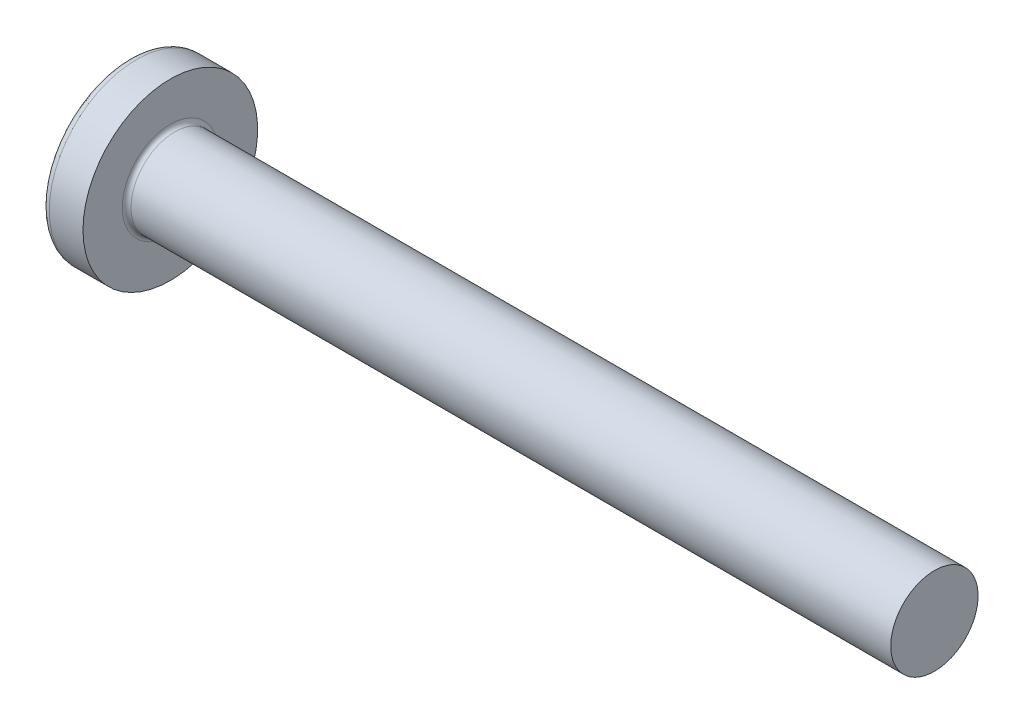
SolidWorks part; units mm, degrees
material "普通碳钢"
ref_plane "Plane1" through (0, 0, 0) normal (0, 0, 1) x (1, 0, 0)
ref_plane "Plane2" through (0, 0, 0) normal (0, 1, 0) x (1, 0, 0)
ref_plane "Plane3" through (0, 0, 0) normal (1, 0, 0) x (0, 0, -1)
sketch "BodySke" plane through (0, 0, 0) normal (0, 0, 1) x (1, 0, 0)
  line L0 (3.1, 2) -> (3.1, 4)
  line L1 (3.45, 6.35) -> (3.45, -3.175) construction
  line L2 (-25.4, 0) -> (127, 0) construction
  line L3 (38.1, 0) -> (0, 0)
  line L4 (3.1, 2) -> (38.1, 2)
  line L5 (38.1, 2) -> (38.1, 0)
  line L6 (1.5553, 4) -> (3.1, 4)
  line L8 (32.1, 6.35) -> (32.1, -3.175) construction
  arc A0 (1.2654, 3.8534) -> (0, 0) centre (6.5, 0) ccw
  arc A2 (1.2654, 3.8534) -> (1.5553, 4) centre (1.5553, 3.64) cw
  dimension "Head_fillet_rad" = 0.36
  dimension "Head_crown_rad" = 6.5
  dimension "Head_ht" = 3.1
  dimension "Diameter" = 4
  dimension "Length" = 35
  dimension "Head_dia" = 8
  dimension "Advance" = 0.7
  dimension "Thread_nom" = 6
revolve "Base-Revolve" add sketch "BodySke"
cosmetic thread "ThreadCosmetic" [suppressed]
fillet "Fillet1" radius 0.2 1 edges at (3.1, 0, 2)
sketch "Sketch3" plane through (0, 0, 0) normal (1, 0, 0) x (0, 0, -1)
  line L0 (0.515, -2.15) -> (-0.515, -2.15)
  line L1 (0.515, -2.15) -> (0.515, 2.15)
  line L2 (-0.515, 2.15) -> (0.515, 2.15)
  line L3 (-0.515, 2.15) -> (-0.515, -2.15)
  dimension "D1" = 2.15
  dimension "Cross_dia" = 4.3
  dimension "D2" = 0.515
  dimension "Cross_width" = 1.03
ref_plane "Plane4" through (2.34, 0, 0) normal (1, 0, 0) x (0, 0, -1)
sketch "Sketch4" plane through (2.34, 0, 0) normal (1, 0, 0) x (0, 0, -1)
  line L0 (0.515, -0.9833) -> (-0.515, -0.9833)
  line L1 (0.515, -0.9833) -> (0.515, 0.9833)
  line L2 (-0.515, 0.9833) -> (0.515, 0.9833)
  line L3 (-0.515, 0.9833) -> (-0.515, -0.9833)
  dimension "D1" = 1.03
  dimension "D2" = 1.9666
  dimension "D3" = 0.515
  dimension "D4" = 0.9833
loft "Recess" cut profiles "Sketch3", "Sketch4"
pattern_circular "RecPat" count 2 every 90 about axis through (0, 0, 0) along (1, 0, 0) of "Recess"
sketch "RecCorSke" plane through (0, 0, 0) normal (0, 0, 1) x (1, 0, 0)
  line L0 (-3.175, 0) -> (15.875, 0) construction
  line L1 (-25.4, 0) -> (127, 0) construction
  line L2 (0, 0) -> (0, 1.0146)
  line L3 (0, 1.0146) -> (2.34, 0.851)
  line L4 (2.34, 0.851) -> (2.6165, 0)
  line L5 (2.6165, 0) -> (0, 0)
  dimension "Diameter" = 1.702
  dimension "Depth" = 2.34
  dimension "Draft_angle" = 4
  dimension "Bottom_angle" = 18
revolve "RecessCore" cut sketch "RecCorSke" angle 360 about L0
sketch "ThdSchSke" plane through (0, 0, 0) normal (0, 0, 1) x (1, 0, 0)
  line L0 (27.1, -1.61) -> (26.8269, -2)
  line L1 (27.1, -1.61) -> (27.3731, -2)
  line L2 (27.3731, -2) -> (27.3731, -2.5)
  line L3 (-3.175, 0) -> (5.1513, 0) construction
  line L5 (27.3731, -2.5) -> (26.8269, -2.5)
  line L6 (26.8269, -2.5) -> (26.8269, -2)
  dimension "Thread_minor" = 3.22
  dimension "Diameter" = 4
  dimension "Start" = 27.1
  dimension "SideAngle" = 55
  dimension "VeeAngle" = 70
  dimension "Overcut" = 5
revolve "ThreadSchematic" [suppressed] cut sketch "ThdSchSke" angle 360 about L3
pattern_linear "ThdSchPat" [suppressed]
sketch "草图1" plane through (38.1, 0, 0) normal (1, 0, 0) x (0, 0, -1)
  circle A0 centre (0, 0) radius 2 construction
  circle A1 centre (0, 0) radius 2
equation "\"D1@Sketch3\" = \"Cross_dia@Sketch3\" / 2"
equation "\"D2@Sketch3\" = \"Cross_width@Sketch3\" / 2"
equation "\"Depth@RecCorSke\" = \"Cross_depth@Plane4\""
equation "\"D1@Sketch4\" = \"Cross_width@Sketch3\""
equation "\"D2@Sketch4\" = \"Cross_dia@Sketch3\" - 2.0 * \"Cross_depth@Plane4\" * tan(26.5  * 0.017453292)"
equation "\"D3@Sketch4\" = \"D1@Sketch4\" / 2"
equation "\"D4@Sketch4\" = \"D2@Sketch4\" / 2"
equation "\"Thread_length@ThreadCosmetic\" = ((sgn( (\"Length@BodySke\" - \"Advance@BodySke\" * 2.0 ) - \"Thread_nom@BodySke\" )-1)*( (\"Length@BodySke\" - \"Advance@BodySke\" * 2.0 ) - \"Thread_nom@BodySke\" ))/-2+ \"Thread_nom@BodySke\""
equation "\"Thread_minor@ThdSchSke\" = \"Thread_minor@ThreadCosmetic\""
equation "\"Diameter@ThdSchSke\" = \"Diameter@BodySke\""
equation "\"Overcut@ThdSchSke\" = \"Diameter@BodySke\" * 1.25"
equation "\"Start@ThdSchSke\" = \"Head_ht@BodySke\" + \"Length@BodySke\" - \"Thread_length@ThreadCosmetic\"  '---Non-countersunk---"
equation "\"Num_threads@ThdSchPat\" = int( \"Thread_length@ThreadCosmetic\" / \"Advance@BodySke\" + 0.999 )  + 1"
equation "\"Advance@ThdSchPat\" = \"Thread_length@ThreadCosmetic\" /  (\"Num_threads@ThdSchPat\" - 1) 'relax it"
